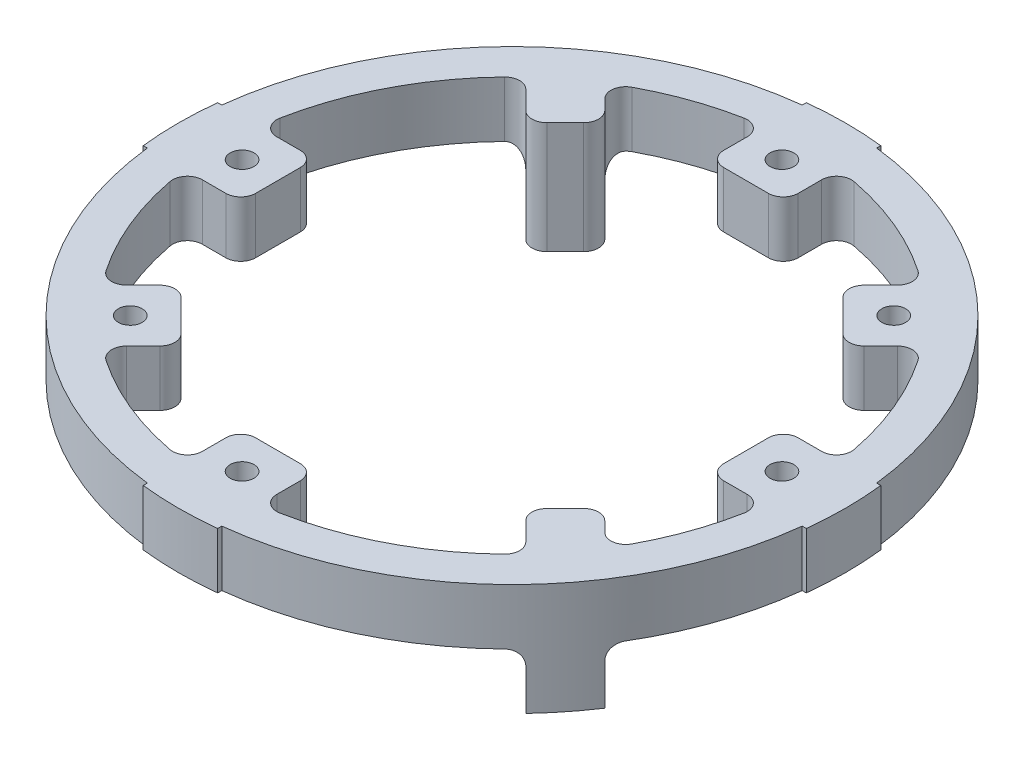
SolidWorks part; units mm, degrees
ref_plane "Front Plane" through (0, 0, 0) normal (0, 0, 1) x (1, 0, 0)
ref_plane "Top Plane" through (0, 0, 0) normal (0, 1, 0) x (1, 0, 0)
ref_plane "Right Plane" through (0, 0, 0) normal (1, 0, 0) x (0, 0, -1)
sketch "Sketch1" plane through (0, 0, 0) normal (0, 1, 0) x (1, 0, 0)
  line L0 (0, 0) -> (44.25, 0) construction
  line L1 (33.4302, 5) -> (36.5864, 5)
  line L2 (33.4302, -5) -> (36.5864, -5)
  line L3 (31.4302, 3) -> (31.4302, -3)
  line L7 (5, -33.4302) -> (5, -36.5864)
  line L8 (3, -31.4302) -> (-3, -31.4302)
  line L9 (-5, -33.4302) -> (-5, -36.5864)
  line L10 (-20.1032, -27.1743) -> (-22.3349, -29.406)
  line L11 (-20.1032, -24.3458) -> (-24.3458, -20.1032)
  line L12 (-27.1743, -20.1032) -> (-29.406, -22.3349)
  line L13 (-33.4302, -5) -> (-36.5864, -5)
  line L14 (-31.4302, -3) -> (-31.4302, 3)
  line L15 (-33.4302, 5) -> (-36.5864, 5)
  line L19 (-5, 33.4302) -> (-5, 36.5864)
  line L20 (-3, 31.4302) -> (3, 31.4302)
  line L21 (5, 33.4302) -> (5, 36.5864)
  line L22 (20.1032, 27.1743) -> (22.3349, 29.406)
  line L23 (20.1032, 24.3458) -> (24.3458, 20.1032)
  line L24 (27.1743, 20.1032) -> (29.406, 22.3349)
  line L25 (-5, 38.9302) -> (-5, 46.441) construction
  line L26 (5, 38.9302) -> (5, 47.4442) construction
  line L27 (-5, 43.9666) -> (-5, 44.5201)
  line L28 (5, 43.9666) -> (5, 44.5201)
  line L29 (43.9666, -5) -> (44.5201, -5)
  line L30 (43.9666, 5) -> (44.5201, 5)
  line L31 (-5, -43.9666) -> (-5, -44.5201)
  line L32 (5, -43.9666) -> (5, -44.5201)
  line L33 (-43.9666, 5) -> (-44.5201, 5)
  line L34 (-43.9666, -5) -> (-44.5201, -5)
  line L35 (-25.7601, 18.689) -> (-18.689, 25.7601) [skipped]
  line L36 (-25.7601, 18.689) -> (-31.0634, 23.9923) [skipped]
  line L37 (-18.689, 25.7601) -> (-23.9923, 31.0634) [skipped]
  line L38 (25.7601, -18.689) -> (31.0634, -23.9923) [skipped]
  line L39 (25.7601, -18.689) -> (18.689, -25.7601) [skipped]
  line L40 (18.689, -25.7601) -> (23.9923, -31.0634) [skipped]
  arc A0 (-43.9666, -5) -> (-5, -43.9666) centre (0, 0) ccw
  circle A1 centre (0, 0) radius 36.25 construction
  circle A2 centre (36.25, 0) radius 1.6
  arc A3 (38.5507, 7.3758) -> (32.475, 22.044) centre (0, 0) ccw
  arc A4 (-36.5864, 5) -> (-38.5507, 7.3758) centre (-36.5864, 7) cw
  circle A5 centre (0, -36.25) radius 1.6
  circle A6 centre (-25.6326, -25.6326) radius 1.6
  circle A7 centre (-36.25, 0) radius 1.6
  arc A8 (-36.5864, -5) -> (-38.5507, -7.3758) centre (-36.5864, -7) ccw
  circle A9 centre (0, 36.25) radius 1.6
  circle A10 centre (25.6326, 25.6326) radius 1.6
  arc A11 (-7.3758, 38.5507) -> (-38.5507, 7.3758) centre (0, 0) ccw
  arc A12 (22.044, 32.475) -> (7.3758, 38.5507) centre (0, 0) ccw
  arc A13 (-29.406, -22.3349) -> (-32.475, -22.044) centre (-30.8202, -20.9207) cw
  arc A14 (-38.5507, -7.3758) -> (-32.475, -22.044) centre (0, 0) ccw
  arc A15 (-22.044, -32.475) -> (-7.3758, -38.5507) centre (0, 0) ccw
  arc A16 (7.3758, -38.5507) -> (38.5507, -7.3758) centre (0, 0) ccw
  arc A17 (-22.3349, -29.406) -> (-22.044, -32.475) centre (-20.9207, -30.8202) ccw
  arc A18 (-44.5201, 5) -> (-44.5201, -5) centre (0, 0) ccw
  arc A19 (-5, -44.5201) -> (5, -44.5201) centre (0, 0) ccw
  arc A20 (-5, 43.9666) -> (-43.9666, 5) centre (0, 0) ccw
  arc A21 (5, 44.5201) -> (-5, 44.5201) centre (0, 0) ccw
  arc A22 (43.9666, 5) -> (5, 43.9666) centre (0, 0) ccw
  arc A23 (44.5201, -5) -> (44.5201, 5) centre (0, 0) ccw
  arc A24 (5, -43.9666) -> (43.9666, -5) centre (0, 0) ccw
  circle A25 centre (-25.6326, 25.6326) radius 1.6 [skipped]
  circle A26 centre (25.6326, -25.6326) radius 1.6 [skipped]
  arc A27 (-5, -36.5864) -> (-7.3758, -38.5507) centre (-7, -36.5864) cw
  arc A28 (5, -36.5864) -> (7.3758, -38.5507) centre (7, -36.5864) ccw
  arc A29 (36.5864, -5) -> (38.5507, -7.3758) centre (36.5864, -7) cw
  arc A30 (36.5864, 5) -> (38.5507, 7.3758) centre (36.5864, 7) ccw
  arc A31 (29.406, 22.3349) -> (32.475, 22.044) centre (30.8202, 20.9207) cw
  arc A32 (22.3349, 29.406) -> (22.044, 32.475) centre (20.9207, 30.8202) ccw
  arc A33 (5, 36.5864) -> (7.3758, 38.5507) centre (7, 36.5864) cw
  arc A34 (-5, 36.5864) -> (-7.3758, 38.5507) centre (-7, 36.5864) ccw
  arc A35 (-5, 33.4302) -> (-3, 31.4302) centre (-3, 33.4302) ccw
  arc A36 (3, 31.4302) -> (5, 33.4302) centre (3, 33.4302) ccw
  arc A37 (20.1032, 27.1743) -> (20.1032, 24.3458) centre (21.5174, 25.7601) ccw
  arc A38 (24.3458, 20.1032) -> (27.1743, 20.1032) centre (25.7601, 21.5174) ccw
  arc A39 (33.4302, 5) -> (31.4302, 3) centre (33.4302, 3) ccw
  arc A40 (33.4302, -5) -> (31.4302, -3) centre (33.4302, -3) cw
  arc A41 (5, -33.4302) -> (3, -31.4302) centre (3, -33.4302) ccw
  arc A42 (-3, -31.4302) -> (-5, -33.4302) centre (-3, -33.4302) ccw
  arc A43 (-20.1032, -27.1743) -> (-20.1032, -24.3458) centre (-21.5174, -25.7601) ccw
  arc A44 (-24.3458, -20.1032) -> (-27.1743, -20.1032) centre (-25.7601, -21.5174) ccw
  arc A45 (-33.4302, -5) -> (-31.4302, -3) centre (-33.4302, -3) ccw
  arc A46 (-31.4302, 3) -> (-33.4302, 5) centre (-33.4302, 3) ccw
  point P55 (0, 0)
  point P61 (38.9302, -5)
  point P76 (0, 0)
  point P93 (38.9302, 5)
  point P114 (31.4302, 5)
  point P117 (31.4302, -5)
  dimension "D1" = 88.5
  dimension "D2" = 72.5
  dimension "D3" = 3.2
  dimension "D4" = 5
  dimension "D8" = 89.6
  dimension "D10" = 2
  dimension "D11" = 2
  dimension "D5" = 7.5
  dimension "D6" = 10
  dimension "D7" = 8
  dimension "D9" = 4
extrude "Boss-Extrude1" add sketch "Sketch1" along normal blind 7.5
sketch "Sketch2" plane through (0, 7.5, 0) normal (0, 1, 0) x (1, 0, 0)
  line L0 (-30.3487, 32.2028) -> (-22.9241, 24.7781)
  line L1 (-24.4326, 36.8932) -> (-17.6208, 30.0814)
  line L2 (-31.4302, 5) -> (5, -31.4302) construction
  line L3 (-20.0957, 24.7781) -> (-17.6208, 27.253)
  line L4 (24.7781, -20.0957) -> (27.253, -17.6208)
  line L5 (24.7781, -22.9241) -> (32.2028, -30.3487)
  line L6 (30.0814, -17.6208) -> (36.8932, -24.4326)
  line L7 (-34.6706, 5) -> (-31.4302, 5) construction
  line L8 (-36.5864, 5) -> (-33.4302, 5) construction
  line L9 (-31.4302, 2.1599) -> (-31.4302, 5) construction
  line L10 (-31.4302, 3) -> (-31.4302, -3) construction
  line L11 (0.4052, -31.4302) -> (5, -31.4302) construction
  line L12 (-3, -31.4302) -> (3, -31.4302) construction
  line L13 (5, -31.4302) -> (5, -34.315) construction
  arc A0 (27.253, -17.6208) -> (30.0814, -17.6208) centre (28.6672, -19.035) cw
  arc A1 (24.7781, -20.0957) -> (24.7781, -22.9241) centre (26.1924, -21.5099) ccw
  arc A2 (5, -43.9666) -> (43.9666, -5) centre (0, 0) ccw construction
  arc A3 (-5, 43.9666) -> (-43.9666, 5) centre (0, 0) ccw construction
  arc A4 (-24.4326, 36.8932) -> (-30.3487, 32.2028) centre (0, 0) ccw
  arc A5 (32.2028, -30.3487) -> (36.8932, -24.4326) centre (0, 0) ccw
  arc A6 (-20.0957, 24.7781) -> (-22.9241, 24.7781) centre (-21.5099, 26.1924) cw
  arc A7 (-17.6208, 27.253) -> (-17.6208, 30.0814) centre (-19.035, 28.6672) ccw
  point P31 (28.6672, -16.2066)
  point P34 (23.3639, -21.5099)
  dimension "D5" = 2
  dimension "D1" = 7.5
  dimension "D2" = 20
  dimension "D3" = 12.5
  dimension "D4" = 12.5
extrude "Boss-Extrude2" add sketch "Sketch2" against normal blind 15
sketch "Sketch3" plane through (0.927, 0, -0.927) normal (-0.7071, 0, 0.7071) x (0.7071, 0, 0.7071)
  line L0 (0, 0) -> (0, -8.9418) construction
  line L1 (-44.25, 0) -> (-34.6246, 0) construction
  circle A0 centre (-38, -4.5) radius 1.6
  circle A1 centre (38, -4.5) radius 1.6
  dimension "D1" = 3.2
  dimension "D2" = 76
  dimension "D3" = 4.5
extrude "Cut-Extrude1" cut sketch "Sketch3" against normal blind 15
fillet "Fillet3" radius 2 2 edges at (28.6655, 3.75, 26.8114) (30.4341, 0, 28.5801)
fillet "Fillet4" radius 2 2 edges at (33.2759, 3.75, 20.8153) (35.0846, 0, 22.6239)
fillet "Fillet5" radius 2 2 edges at (-20.8153, 3.75, -33.2759) (-22.6239, 0, -35.0846)
fillet "Fillet6" radius 2 2 edges at (-26.8114, 3.75, -28.6655) (-28.5801, 0, -30.4341)
